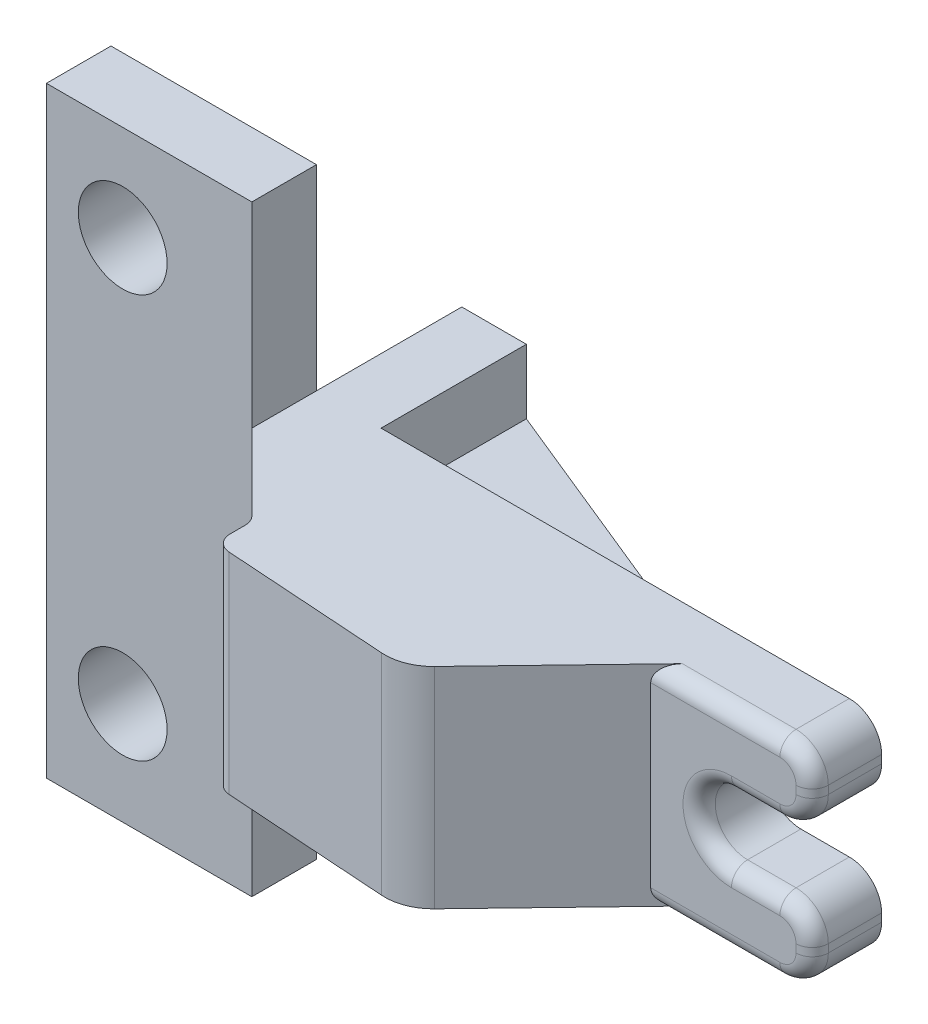
SolidWorks part; units mm, degrees
ref_plane "前视基准面" through (0, 0, 0) normal (0, 0, 1) x (1, 0, 0)
ref_plane "上视基准面" through (0, 0, 0) normal (0, 1, 0) x (1, 0, 0)
ref_plane "右视基准面" through (0, 0, 0) normal (1, 0, 0) x (0, 0, -1)
sketch "草图2" plane through (0, 0, 0) normal (0, 0, 1) x (1, 0, 0)
  line L0 (38.5, -0.2109) -> (25.7753, -0.2109) construction
  line L1 (38.5, 18.4222) -> (25.7753, 18.4222)
  line L2 (38.5, 18.4222) -> (38.5, -18.844)
  line L3 (38.5, -18.844) -> (25.7753, -18.844)
  line L4 (25.7753, 18.4222) -> (25.7753, -18.844)
  line L5 (38.5, -21.5) -> (38.5, 21.5) construction
  line L6 (38.5, 18.4222) -> (38.5, -18.844)
  circle A0 centre (30.5, -12.5) radius 2.75
  circle A1 centre (30.5, 12.5) radius 2.75
  line M2 (38.5, -21.5) -> (38.5, 21.5)
  circle M9 centre (30.5, 12.5) radius 2.5
  circle M10 centre (30.5, -12.5) radius 2.5
  dimension "D1" = 5.5
  dimension "D2" = 5.5
extrude "凸台-拉伸1" add sketch "草图2" along normal blind 4 contours L0 L6 L1 L4 M9 | L0 L4 L3 M2 M10
sketch "草图3" plane through (0, 230.9088, 0) normal (0, 0, 1) x (-1, 0, 0)
  line L0 (-43.5, 237.6197) -> (-43.5, 224.6197)
  line L11 (-43.5, 237.6197) -> (-38.5, 237.6197)
  line L13 (-38.5, 237.6197) -> (-38.5, 224.6197)
  line L14 (-38.5, 224.6197) -> (-43.5, 224.6197)
  dimension "D1" = 13
extrude "凸台-拉伸2" add sketch "草图3" along normal up to surface (4 mm away) up to face at (32.1376, -0.2109, 4)
sketch "草图4" plane through (0, 0, 0) normal (0, 0, 1) x (1, 0, 0)
  line L0 (38.5, -6.7109) -> (43.5, -6.7109) construction
  line L1 (43.5, 6.2891) -> (38.5, 6.2891)
  line L2 (43.5, 6.2891) -> (43.5, -6.7109)
  line L3 (43.5, -6.7109) -> (38.5, -6.7109)
  line L4 (38.5, 6.2891) -> (38.5, -6.7109)
extrude "凸台-拉伸4" add sketch "草图4" against normal blind 9
sketch "草图5" plane through (43.5, 0, 0) normal (1, 0, 0) x (0, 0, -1)
  line L0 (-4, 6.2891) -> (9, 6.2891) construction
  line L1 (9, -6.7109) -> (-4.3, -6.7109)
  line L2 (9, -6.7109) -> (9, 6.2891)
  line L3 (9, 6.2891) -> (-4.3, 6.2891)
  line L4 (-4.3, -6.7109) -> (-4.3, 6.2891)
  line L5 (-4, 6.2891) -> (-4, 18.4222) construction
  dimension "D1" = 0.3
extrude "凸台-拉伸5" add sketch "草图5" along normal blind 30
sketch "草图9" plane through (0, 0, 4.3) normal (0, 0, 1) x (1, 0, 0)
  line L0 (73.5, -0.2109) -> (69.5234, -0.2109) construction
  line L1 (73.5, 6.2891) -> (73.5, -6.7109) construction
  line L3 (68.5, 1.7891) -> (73.5, 1.7891)
  line L5 (68.5, -2.2109) -> (73.5, -2.2109)
  line L6 (73.5, 1.7891) -> (73.5, -2.2109)
  arc A0 (68.5, -2.2109) -> (68.5, 1.7891) centre (68.5, -0.2109) cw
  point P4 (83.8418, -0.2109)
  dimension "D1" = 4
  dimension "D2" = 5
extrude "切除-拉伸2" cut sketch "草图9" against normal through all
sketch "草图10" plane through (0, -6.7109, 0) normal (0, -1, 0) x (1, 0, 0)
  line L0 (43.5, 11.2868) -> (55.973, 12.1303)
  line L1 (73.5, 4.3) -> (43.5, 4.3) construction
  line L2 (55.973, 12.1303) -> (63.5, 4.3)
  line L3 (63.5, 4.3) -> (43.5, 4.3)
  line L4 (73.5, 4.3) -> (73.5, -9) construction
  line L5 (43.5, 4.3) -> (43.5, 11.2868)
  line L6 (43.5, 4.3) -> (43.5, 4) construction
  point P0 (43.4523, 11.2836)
  dimension "D1" = 10
  dimension "D3" = 130
extrude "凸台-拉伸6" add sketch "草图10" against normal up to surface (13 mm away) up to face at (49.9286, 6.2891, -0.2)
fillet "圆角4" radius 3 1 edges at (55.973, -0.2109, 12.1303)
sketch "草图8" plane through (0, 6.2891, 0) normal (0, 1, 0) x (1, 0, 0)
  line L0 (73.5, 9) -> (38.5, 9) construction
  line L2 (38.5, 9) -> (73.5, 9) construction
  line L3 (73.5, 2.35) -> (73.5, 9)
  line L4 (73.5, 9) -> (73.5, -4.3) construction
  line L5 (73.5, 9) -> (42.7664, 9)
  spline S0 degree 2 poles (42.7664, 9) (59.1682, 9) (73.5, 2.35) knots 0 0 0 1 1 1
sketch "草图12" plane through (0, -6.7109, 0) normal (0, -1, 0) x (1, 0, 0)
  line L1 (42.5, 0) -> (73.5, 0)
  line L2 (42.5, 0) -> (42.5, -9)
  line L3 (42.5, -9) -> (73.5, -9)
  line L4 (73.5, 0) -> (73.5, -9)
  line L5 (38.5, -9) -> (38.5, 0) construction
  line L6 (38.5, 0) -> (25.7753, 0) construction
  dimension "D1" = 4
extrude "切除-拉伸3" cut sketch "草图12" against normal through all
ref_plane "基准面1" through (0, -0.2109, 0) normal (0, -1, 0) x (-1, 0, 0)
sketch "草图13" plane through (0, -0.2109, 0) normal (0, -1, 0) x (-1, 0, 0)
  line L0 (-64.5394, 0) -> (-42.5, 9)
rib "筋1" sketch "草图13" sketch "草图13" thickness 5 extrusion direction parallel to sketch draft on no parameters "D1"=5
chamfer "倒角1" distance 5 angle 45 1 edges at (43.5, -0.2109, 4)
fillet "圆角5" radius 1 2 edges at (43.5, -0.2109, 9) (43.5, -0.2109, 11.2868)
fillet "圆角6" radius 2 4 edges at (73.5, 1.7891, 2.15) (73.5, -2.2109, 2.15) (73.5, 6.2891, 2.15) (73.5, -6.7109, 2.15)
fillet "圆角7" radius 1 11 edges at (67.5, 6.2891, 4.3) (72.9142, 5.7033, 4.3) (73.5, 4.0391, 4.3) (72.9142, 2.3749, 4.3) (70, 1.7891, 4.3) (66.5, -0.2109, 4.3) (70, -2.2109, 4.3) (72.9142, -2.7967, 4.3) (73.5, -4.4609, 4.3) (72.9142, -6.1251, 4.3) (67.5, -6.7109, 4.3)
